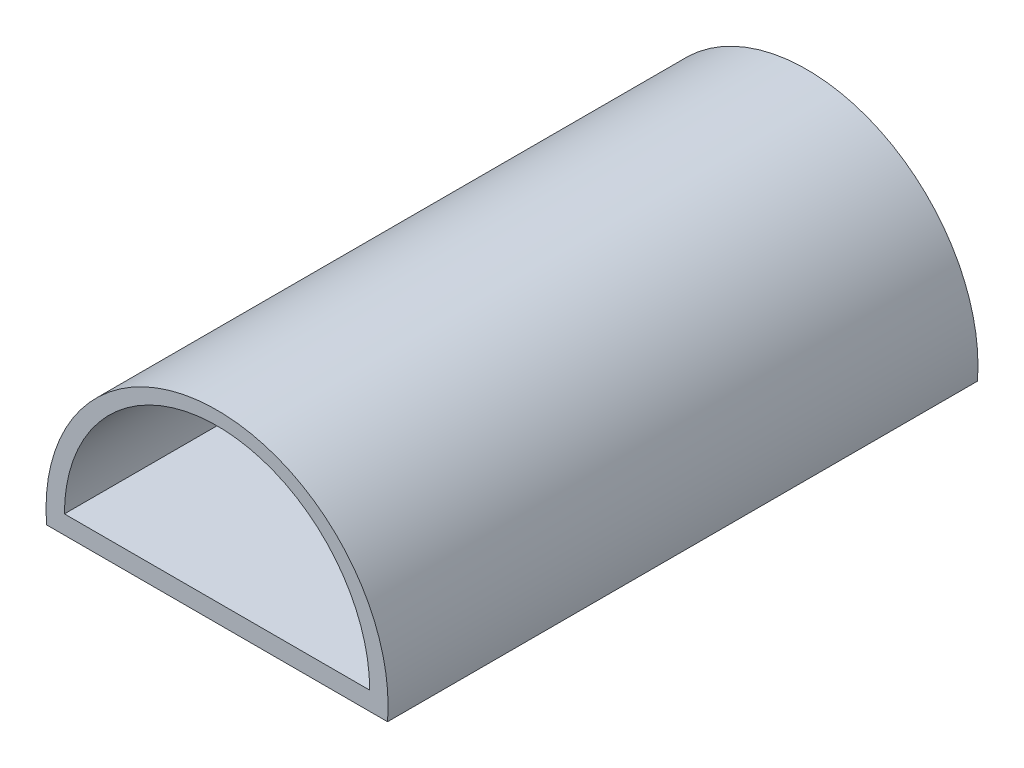
SolidWorks part; units mm, degrees
material "PVC 0.007 Plasticized"
ref_plane "Front Plane" through (0, 0, 0) normal (0, 0, 1) x (1, 0, 0)
ref_plane "Top Plane" through (0, 0, 0) normal (0, 1, 0) x (1, 0, 0)
ref_plane "Right Plane" through (0, 0, 0) normal (1, 0, 0) x (0, 0, -1)
sketch "Sketch1" plane through (0, 0, 0) normal (0, 0, 1) x (1, 0, 0)
  line L0 (-23.1114, -10.0484) -> (6.2574, -10.0484)
  line L2 (-8.427, -8.4609) -> (-21.5715, -8.4609)
  line L3 (-8.427, -8.4609) -> (4.7175, -8.4609)
  arc A0 (-23.1114, -10.0484) -> (6.2574, -10.0484) centre (-8.427, -8.8769) cw
  arc A1 (-21.5715, -8.4609) -> (4.7175, -8.4609) centre (-8.427, -8.4609) cw
extrude "Boss-Extrude2" add sketch "Sketch1" along normal blind 50.8
